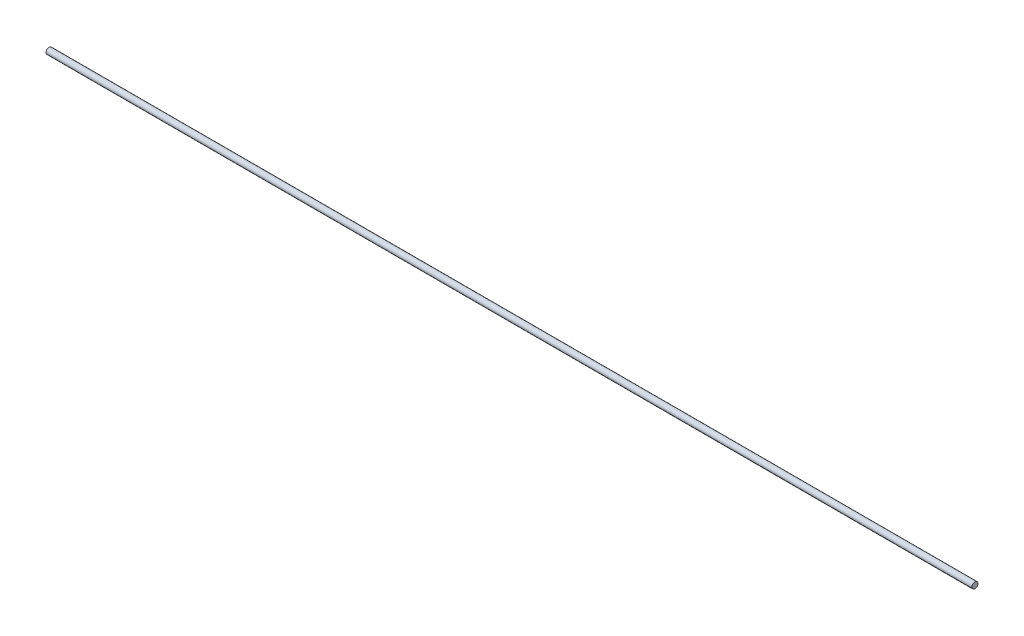
SolidWorks part; units mm, degrees
ref_plane "Alzado" through (0, 0, 0) normal (0, 0, 1) x (1, 0, 0)
ref_plane "Planta" through (0, 0, 0) normal (0, 1, 0) x (1, 0, 0)
ref_plane "Vista lateral" through (0, 0, 0) normal (1, 0, 0) x (0, 0, -1)
sketch "Croquis1" plane through (0, 0, 0) normal (1, 0, 0) x (0, 0, -1)
  circle A0 centre (0, 0) radius 4
extrude "Saliente-Extruir1" add sketch "Croquis1" along normal mid plane 1215.63
